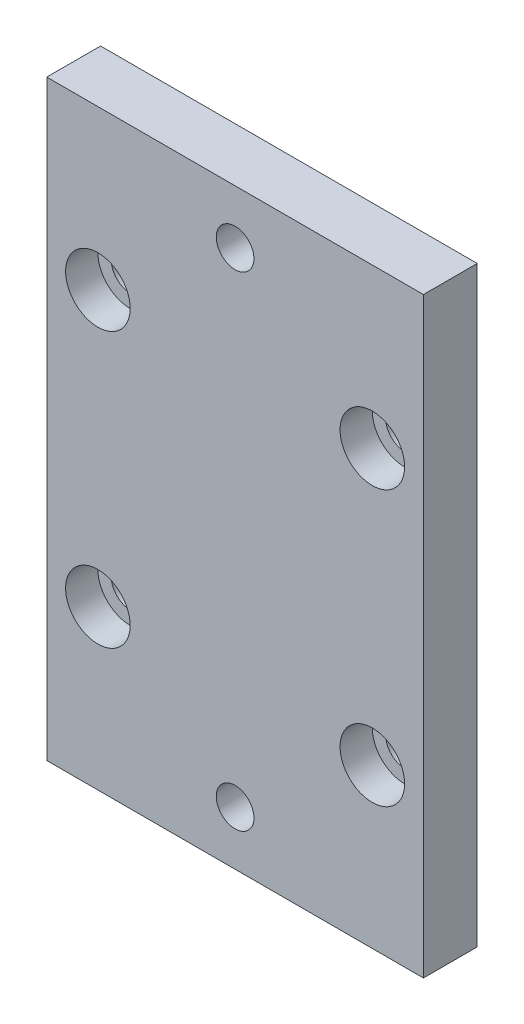
SolidWorks part; units mm, degrees
ref_plane "Front Plane" through (0, 0, 0) normal (0, 0, 1) x (1, 0, 0)
ref_plane "Top Plane" through (0, 0, 0) normal (0, 1, 0) x (1, 0, 0)
ref_plane "Right Plane" through (0, 0, 0) normal (1, 0, 0) x (0, 0, -1)
sketch "Sketch1" plane through (0, 0, 0) normal (0, 0, 1) x (1, 0, 0)
  line L1 (0, 0) -> (35, 0)
  line L2 (0, 0) -> (0, 55)
  line L3 (0, 55) -> (35, 55)
  line L4 (35, 0) -> (35, 55)
  circle A0 centre (4.75, 40.25) radius 1.75
  circle A1 centre (30.25, 40.25) radius 1.75
  circle A2 centre (30.25, 14.75) radius 1.75
  circle A3 centre (4.75, 14.75) radius 1.75
  circle A4 centre (17.5, 50) radius 1.75
  circle A5 centre (17.5, 5) radius 1.75
  dimension "D3" = 4.75
  dimension "D4" = 14.75
  dimension "D5" = 3.5
  dimension "D8" = 3.5
  dimension "D9" = 3.5
  dimension "D10" = 17.5
  dimension "D11" = 5
  dimension "D12" = 5
  dimension "D13" = 17.5
  dimension "D1" = 55
  dimension "D2" = 35
  dimension "D6" = 2
  dimension "D7" = 2
extrude "Boss-Extrude1" add sketch "Sketch1" along normal blind 5
sketch "Sketch2" plane through (0, 0, 5) normal (0, 0, 1) x (1, 0, 0)
  circle A0 centre (4.75, 40.25) radius 3
  circle A1 centre (30.25, 40.25) radius 3
  circle A2 centre (30.25, 14.75) radius 3
  circle A3 centre (4.75, 14.75) radius 3
  dimension "D1" = 6
  dimension "D2" = 2
  dimension "D3" = 2
extrude "Cut-Extrude1" cut sketch "Sketch2" against normal blind 3
chamfer "Chamfer1" distance 2 angle 45 2 edges at (19.25, 5, 0) (19.25, 50, 0)
